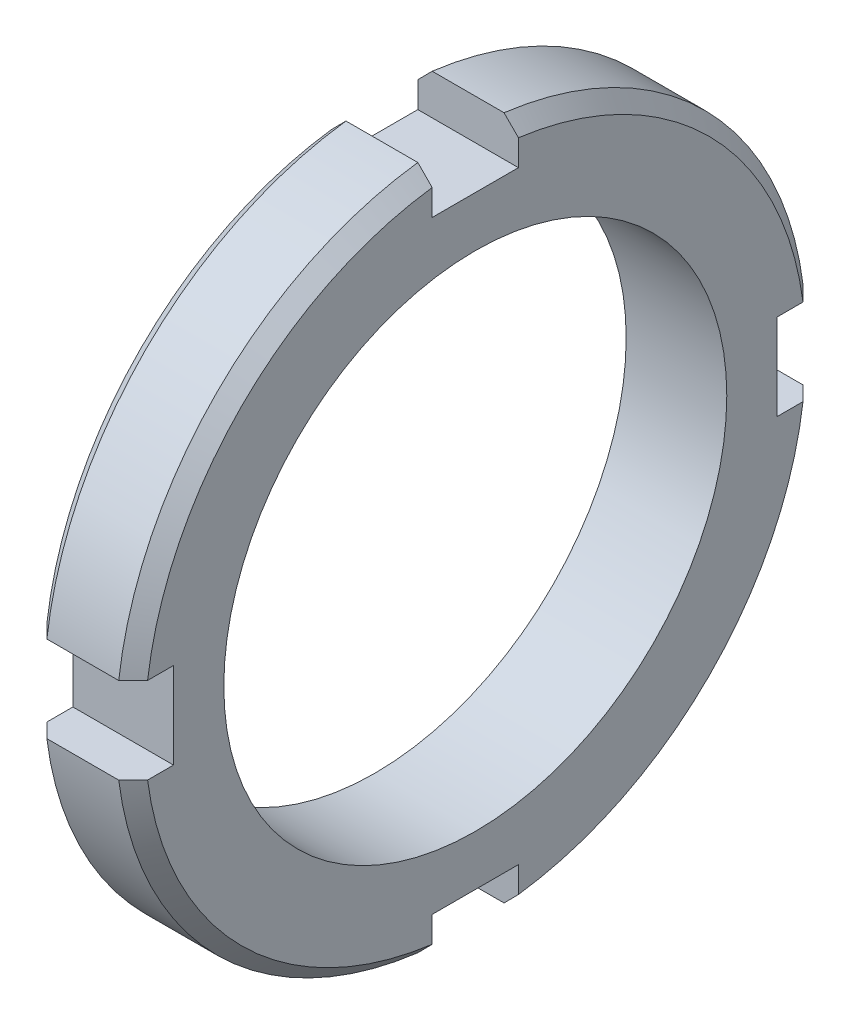
SolidWorks part; units mm, degrees
ref_plane "前视基准面" through (0, 0, 0) normal (0, 0, 1) x (1, 0, 0)
ref_plane "上视基准面" through (0, 0, 0) normal (0, 1, 0) x (1, 0, 0)
ref_plane "右视基准面" through (0, 0, 0) normal (1, 0, 0) x (0, 0, -1)
other "Configuration Table"
sketch "草图1" plane through (0, 0, 0) normal (0, 0, 1) x (1, 0, 0)
  line L0 (-5, 0) -> (12, 0) construction
  line L1 (0, 17.5) -> (0, 23)
  line L2 (0, 23) -> (1, 24)
  line L3 (1, 24) -> (6, 24)
  line L4 (6, 24) -> (7, 23)
  line L5 (7, 23) -> (7, 17.5)
  line L6 (7, 17.5) -> (0, 17.5)
revolve "01_RING" add sketch "草图1" angle 360 about L0
ref_plane "P_SLOTS" through (-0.5, 0, 0) normal (1, 0, 0) x (0, 0, -1)
sketch "草图2" plane through (-0.5, 0, 0) normal (1, 0, 0) x (0, 0, -1)
  line L0 (21, -3) -> (26, -3)
  line L1 (26, -3) -> (26, 3)
  line L2 (26, 3) -> (21, 3)
  line L3 (21, 3) -> (21, -3)
  line L4 (-26, -3) -> (-21, -3)
  line L5 (-21, -3) -> (-21, 3)
  line L6 (-21, 3) -> (-26, 3)
  line L7 (-26, 3) -> (-26, -3)
  line L8 (-3, 21) -> (3, 21)
  line L9 (3, 21) -> (3, 26)
  line L10 (3, 26) -> (-3, 26)
  line L11 (-3, 26) -> (-3, 21)
  line L12 (-3, -26) -> (3, -26)
  line L13 (3, -26) -> (3, -21)
  line L14 (3, -21) -> (-3, -21)
  line L15 (-3, -21) -> (-3, -26)
extrude "02_SLOTS" cut sketch "草图2" along normal blind 8
